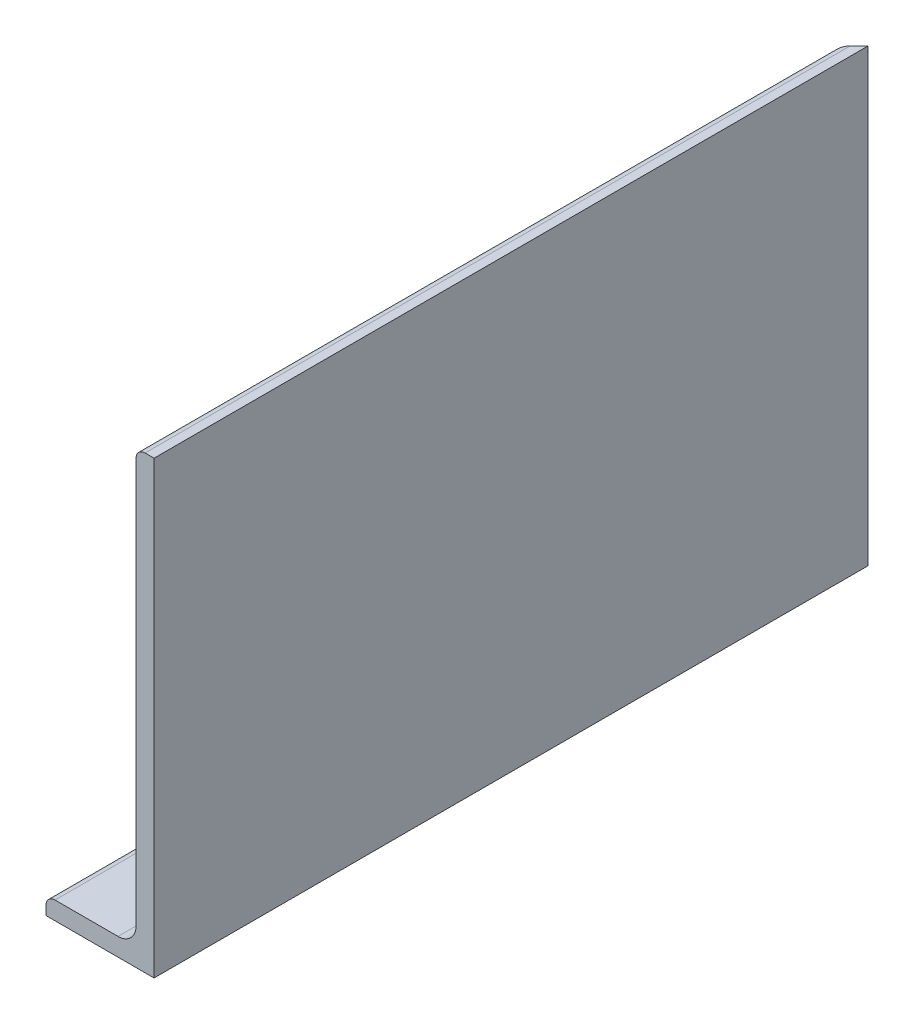
SolidWorks part; units mm, degrees
ref_plane "Front Plane" through (0, 0, 0) normal (0, 0, 1) x (1, 0, 0)
ref_plane "Top Plane" through (0, 0, 0) normal (0, 1, 0) x (1, 0, 0)
ref_plane "Right Plane" through (0, 0, 0) normal (1, 0, 0) x (0, 0, -1)
sketch "Sketch1" plane through (0, 0, 0) normal (0, 0, 1) x (1, 0, 0)
  line L0 (293.5291, -14.2714) -> (293.5291, -64.2714)
  line L1 (293.5291, -64.2714) -> (281.5291, -64.2714)
  line L2 (281.5291, -64.2714) -> (281.5291, -62.2714)
  line L3 (281.5291, -62.2714) -> (291.5291, -62.2714)
  line L4 (291.5291, -62.2714) -> (291.5291, -14.2714)
  line L5 (291.5291, -14.2714) -> (293.5291, -14.2714)
  dimension "D1" = 2
  dimension "D2" = 2
  dimension "D3" = 50
  dimension "D4" = 12
extrude "Boss-Extrude1" add sketch "Sketch1" along normal blind 79.29
fillet "Fillet1" radius 1 2 edges at (281.5291, -62.2714, 39.645) (291.5291, -14.2714, 39.645)
fillet "Fillet2" radius 2 1 edges at (291.5291, -62.2714, 39.645)
sketch "Sketch2" plane through (0, -62.2714, 0) normal (0, 1, 0) x (1, 0, 0)
  line L0 (281.5291, -79.29) -> (281.5291, 0) construction
  line L1 (289.5291, 0) -> (282.5291, 0) construction
  line L2 (289.5291, -79.29) -> (282.5291, -79.29) construction
  circle A0 centre (286.0291, -20) radius 1.6
  circle A1 centre (286.0291, -59.29) radius 1.6
  dimension "D1" = 3.2
  dimension "D2" = 3.2
  dimension "D3" = 4.5
  dimension "D4" = 20
  dimension "D5" = 4.5
  dimension "D6" = 20
extrude "Cut-Extrude1" cut sketch "Sketch2" against normal through all
sketch "Sketch3" plane through (0, -62.2714, 0) normal (0, 1, 0) x (1, 0, 0)
  line L4 (293.5291, 0) -> (281.3316, -12.1975)
  line L5 (281.3316, -12.1975) -> (281.3316, 1.1182)
  line L6 (281.3316, 1.1182) -> (293.5291, 1.1182)
  line L7 (293.5291, 1.1182) -> (293.5291, 0)
extrude "Cut-Extrude4" cut sketch "Sketch3" against normal through all both and the other way through all
